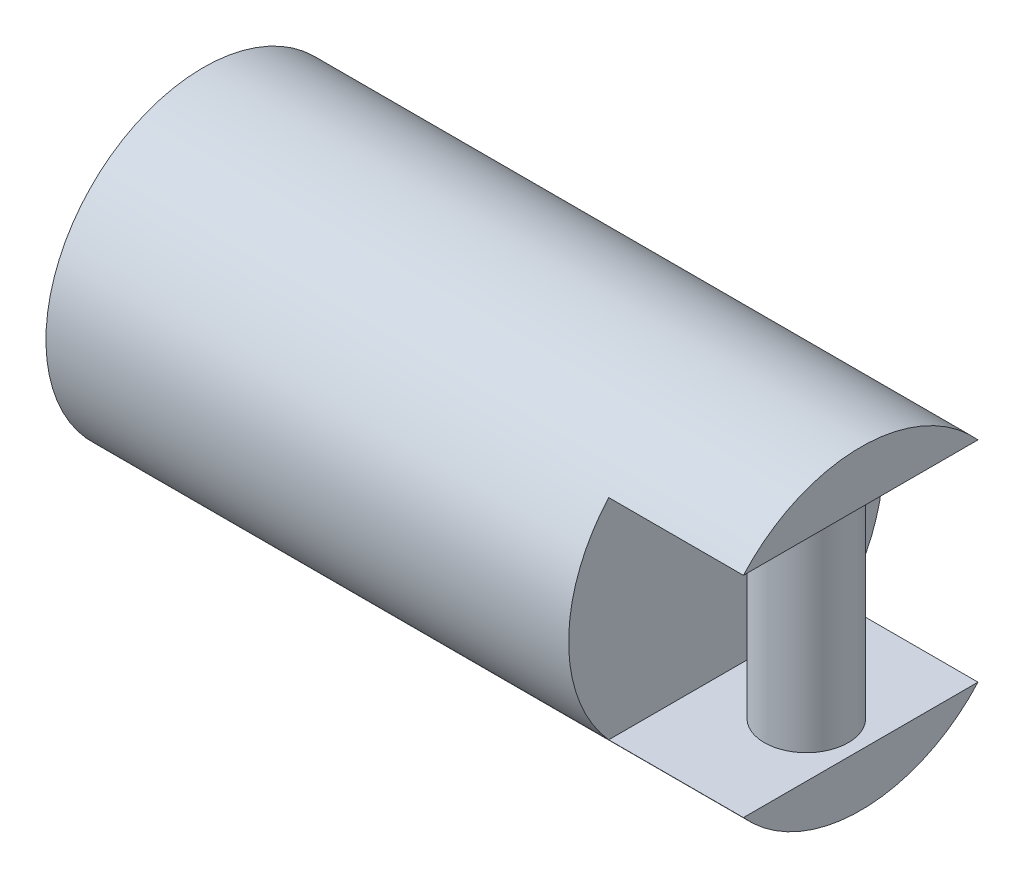
SolidWorks part; units mm, degrees
ref_plane "前视基准面" through (0, 0, 0) normal (0, 0, 1) x (1, 0, 0)
ref_plane "上视基准面" through (0, 0, 0) normal (0, 1, 0) x (1, 0, 0)
ref_plane "右视基准面" through (0, 0, 0) normal (1, 0, 0) x (0, 0, -1)
sketch "草图2" plane through (0, 0, 0) normal (1, 0, 0) x (0, 0, -1)
  circle A0 centre (0, 0) radius 22.5
  dimension "D1" = 45
extrude "凸台-拉伸1" add sketch "草图2" along normal blind 94
sketch "草图3" plane through (0, 0, 0) normal (0, 0, 1) x (1, 0, 0)
  line L0 (94, -22.5) -> (94, 22.5) construction
  line L1 (94, 0) -> (74.7369, 0)
  line L2 (94, 0) -> (94, 15)
  line L3 (94, 15) -> (74.7369, 15)
  line L4 (74.7369, 0) -> (74.7369, 15)
  line L6 (94, 0) -> (74.7369, 0)
  line L7 (94, 0) -> (94, -15)
  line L8 (94, -15) -> (74.7369, -15)
  line L9 (74.7369, 0) -> (74.7369, -15)
  dimension "D1" = 15
  dimension "D2" = 15
extrude "切除-拉伸1" cut sketch "草图3" against normal blind 53 and the other way blind 53 contours L4 L1 L2 L3 | L1 L9 L8 L7
sketch "草图4" plane through (0, 0, 0) normal (0, 1, 0) x (1, 0, 0)
  line L0 (-4.5992, 0) -> (99.4992, 0)
  circle A0 centre (86.2244, 0) radius 6
extrude "凸台-拉伸3" add sketch "草图4" along normal blind 16 and the other way blind 19 contours L0 A0 | L0 A0
